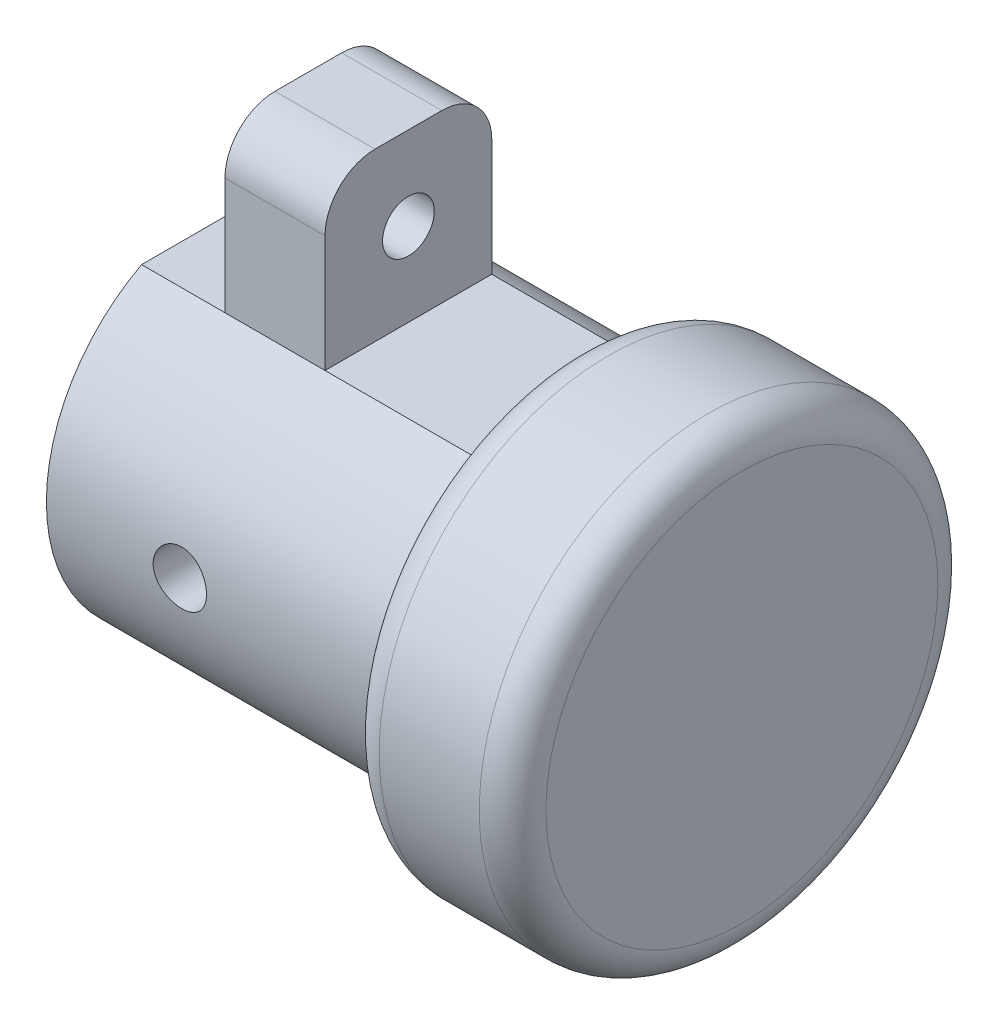
SolidWorks part; units mm, degrees
ref_plane "Front Plane" through (0, 0, 0) normal (0, 0, 1) x (1, 0, 0)
ref_plane "Top Plane" through (0, 0, 0) normal (0, 1, 0) x (1, 0, 0)
ref_plane "Right Plane" through (0, 0, 0) normal (1, 0, 0) x (0, 0, -1)
sketch "Sketch1" plane through (0, 0, 0) normal (1, 0, 0) x (0, 0, -1)
  line L1 (-5, 9.4712) -> (5, 9.4712)
  line L2 (-5, 9.4712) -> (-5, 19.4712)
  line L3 (-5, 19.4712) -> (5, 19.4712)
  line L4 (5, 9.4712) -> (5, 19.4712)
  circle A0 centre (0, 0) radius 7.71
  circle A1 centre (0, 0) radius 10.71
  dimension "D1" = 15.42
  dimension "D3" = 10
  dimension "D4" = 10
  dimension "D2" = 3
extrude "Boss-Extrude1" add sketch "Sketch1" along normal blind 16 contours A1 L4 L3 L2 | A0
sketch "Sketch2" plane through (16, 0, 11) normal (-1, 0, 0) x (0, 0, 1)
  line L0 (-6, 19.4712) -> (-16, 9.4712) construction
  line L3 (-16, 9.4712) -> (-16, 19.4712) construction
  line L5 (-16, 19.4712) -> (-6, 9.4712) construction
  circle A0 centre (-11, 14.4712) radius 1.55
  dimension "D1" = 3.1
extrude "Cut-Extrude1" cut sketch "Sketch2" along normal through all
ref_plane "Plane1" through (0, 0, 10.71) normal (0, 0, 1) x (1, 0, 0)
sketch "Sketch3" plane through (0, 0, 10.71) normal (0, 0, 1) x (1, 0, 0)
  line L1 (16, -10.71) -> (16, 9.4712) construction
  circle A0 centre (8, 0) radius 1.6
  dimension "D1" = 3.2
  dimension "D2" = 8
extrude "Cut-Extrude2" cut sketch "Sketch3" against normal through all
sketch "Sketch4" plane through (0, 19.4712, 0) normal (0, 1, 0) x (1, 0, 0)
  line L0 (16, -5) -> (0, -5) construction
  line L1 (0, 5) -> (5, 5)
  line L2 (0, 5) -> (0, -5)
  line L3 (0, -5) -> (5, -5)
  line L4 (5, 5) -> (5, -5)
  line L6 (16, 5) -> (11, 5)
  line L7 (16, 5) -> (16, -5)
  line L8 (16, -5) -> (11, -5)
  line L9 (11, 5) -> (11, -5)
  dimension "D1" = 5
  dimension "D2" = 5
extrude "Cut-Extrude4" cut sketch "Sketch4" against normal up to vertex (9.606 mm away)
fillet "Fillet1" radius 3 2 edges at (8, 19.4712, 5) (8, 19.4712, -5)
sketch "Sketch8" plane through (16, 0, 0) normal (1, 0, 0) x (0, 0, -1)
  line L2 (5, 9.4712) -> (-5, 9.4712)
  line L3 (5, 9.4712) -> (-5, 9.4712)
  arc A2 (-5, 9.4712) -> (5, 9.4712) centre (0, 0) ccw
  arc A3 (-5, 9.4712) -> (5, 9.4712) centre (0, 0) ccw
  dimension "D1" = 0
extrude "Boss-Extrude2" add sketch "Sketch8" along normal blind 15
sketch "Sketch9" plane through (31, 0, 0) normal (1, 0, 0) x (0, 0, -1)
  circle A0 centre (0, 0) radius 1.5
  dimension "D1" = 3
extrude "Cut-Extrude5" [suppressed] cut sketch "Sketch9" against normal through all
ref_plane "Plane2" through (31, 0, 0) normal (1, 0, 0) x (0, 0, -1)
sketch "Sketch10" plane through (31, 0, 0) normal (1, 0, 0) x (0, 0, -1)
  circle A0 centre (0, 0) radius 1.5
  circle A1 centre (0, 0) radius 13.75
  dimension "D1" = 27.5
  dimension "D2" = 3
extrude "Boss-Extrude3" add sketch "Sketch10" against normal blind 10
fillet "Fillet2" radius 2 2 edges at (31, 0, -13.75) (21, 0, -13.75)
